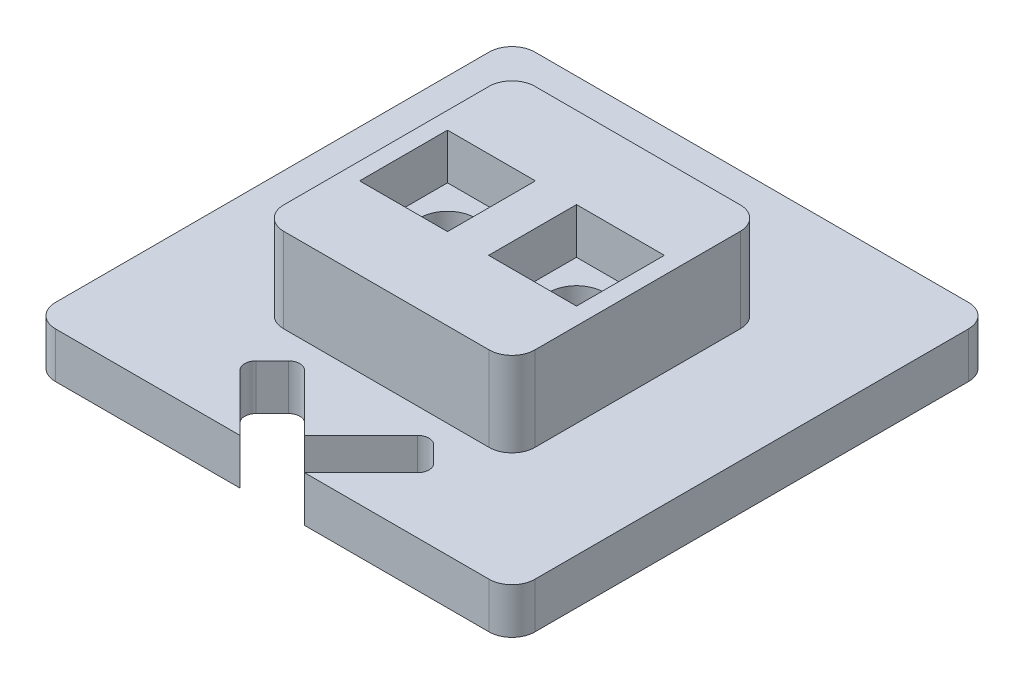
SolidWorks part; units mm, degrees
ref_plane "Front Plane" through (0, 0, 0) normal (0, 0, 1) x (1, 0, 0)
ref_plane "Top Plane" through (0, 0, 0) normal (0, 1, 0) x (1, 0, 0)
ref_plane "Right Plane" through (0, 0, 0) normal (1, 0, 0) x (0, 0, -1)
sketch "Sketch1" plane through (0, 0, 0) normal (0, 1, 0) x (1, 0, 0)
  line L1 (-5.5, -5.5) -> (5.5, -5.5)
  line L2 (-5.5, -5.5) -> (-5.5, 5.5)
  line L3 (-5.5, 5.5) -> (5.5, 5.5)
  line L4 (5.5, -5.5) -> (5.5, 5.5)
  line L5 (-5.5, -5.5) -> (5.5, 5.5) construction
  line L6 (-5.5, 5.5) -> (5.5, -5.5) construction
  point P0 (0, 0)
  dimension "D1" = 11
  dimension "D2" = 11
extrude "Boss-Extrude1" add sketch "Sketch1" along normal blind 3.7
fillet "Fillet1" radius 1 4 edges at (-5.5, 1.85, -5.5) (-5.5, 1.85, 5.5) (5.5, 1.85, -5.5) (5.5, 1.85, 5.5)
sketch "Sketch2" plane through (0, 3.7, 0) normal (0, 1, 0) x (1, 0, 0)
  line L0 (-2.825, 0) -> (2.825, 0) construction
  line L2 (-4.75, -1.925) -> (-0.9, -1.925)
  line L3 (-4.75, -1.925) -> (-4.75, 1.925)
  line L4 (-4.75, 1.925) -> (-0.9, 1.925)
  line L5 (-0.9, -1.925) -> (-0.9, 1.925)
  line L6 (-4.75, -1.925) -> (-0.9, 1.925) construction
  line L7 (-4.75, 1.925) -> (-0.9, -1.925) construction
  line L8 (0.9, -1.925) -> (4.75, -1.925)
  line L9 (0.9, -1.925) -> (0.9, 1.925)
  line L10 (0.9, 1.925) -> (4.75, 1.925)
  line L11 (4.75, -1.925) -> (4.75, 1.925)
  line L12 (0.9, -1.925) -> (4.75, 1.925) construction
  line L13 (0.9, 1.925) -> (4.75, -1.925) construction
  point P4 (0, 0)
  dimension "D1" = 3.85
  dimension "D2" = 3.85
  dimension "D3" = 3.85
  dimension "D4" = 3.85
  dimension "D5" = 5.65
extrude "Cut-Extrude1" cut sketch "Sketch2" against normal blind 2
sketch "Sketch4" plane through (0, 0, 0) normal (0, -1, 0) x (-1, 0, 0)
  line L0 (2.825, 0) -> (-2.825, 0) construction
  circle A0 centre (2.825, 0) radius 2.2
  circle A1 centre (-2.825, 0) radius 2.2
  point P4 (0, 0)
  point P8 (0, 0)
  dimension "D1" = 5.65
  dimension "D2" = 4.4
  dimension "D3" = 4.4
extrude "Boss-Extrude2" add sketch "Sketch4" along normal blind 2
sketch "Sketch5" plane through (0, -2, 0) normal (0, -1, 0) x (-1, 0, 0)
  line L1 (9.5, 10.5) -> (-9.5, 10.5)
  line L2 (10.5, 9.5) -> (10.5, -9.5)
  line L3 (9.5, -10.5) -> (-9.5, -10.5)
  line L4 (-10.5, 9.5) -> (-10.5, -9.5)
  line L5 (10.5, 10.5) -> (-10.5, -10.5) construction
  line L6 (10.5, -10.5) -> (-10.5, 10.5) construction
  arc A0 (10.5, -9.5) -> (9.5, -10.5) centre (9.5, -9.5) cw
  arc A1 (-10.5, -9.5) -> (-9.5, -10.5) centre (-9.5, -9.5) ccw
  arc A2 (-9.5, 10.5) -> (-10.5, 9.5) centre (-9.5, 9.5) ccw
  arc A3 (9.5, 10.5) -> (10.5, 9.5) centre (9.5, 9.5) cw
  point P0 (0, 0)
  dimension "D3" = 1
  dimension "D1" = 21
  dimension "D2" = 21
extrude "Boss-Extrude3" add sketch "Sketch5" against normal blind 2
sketch "Sketch3" plane through (0, 3.7, 0) normal (0, 1, 0) x (1, 0, 0)
  line L0 (-2.825, 0) -> (2.825, 0) construction
  circle A0 centre (-2.825, 0) radius 1.2
  circle A1 centre (2.825, 0) radius 1.2
  point P4 (0, 0)
  point P5 (0, 0)
  point P8 (0, 0)
  dimension "D2" = 2.4
  dimension "D3" = 2.4
  dimension "D1" = 5.65
extrude "Cut-Extrude2" cut sketch "Sketch3" against normal through all
sketch "Sketch7" plane through (0, 0, 0) normal (0, 1, 0) x (1, 0, 0)
  line L0 (9.5, -10.5) -> (-9.5, -10.5) construction
  line L1 (2.8284, -14.7426) -> (4.2426, -13.3284)
  line L2 (2.8284, -14.7426) -> (-3.8891, -8.0251)
  line L3 (-3.8891, -7.318) -> (-3.182, -6.6109)
  line L4 (4.2426, -13.3284) -> (-2.4749, -6.6109)
  line L5 (2.8284, -14.7426) -> (-2.8284, -6.2574) construction
  line L6 (-4.2426, -7.6716) -> (4.2426, -13.3284) construction
  line L8 (-4.2426, -13.3284) -> (-2.8284, -14.7426)
  line L9 (-4.2426, -13.3284) -> (2.4749, -6.6109)
  line L10 (3.182, -6.6109) -> (3.8891, -7.318)
  line L11 (-2.8284, -14.7426) -> (3.8891, -8.0251)
  line L12 (-4.2426, -13.3284) -> (4.2426, -7.6716) construction
  line L13 (2.8284, -6.2574) -> (-2.8284, -14.7426) construction
  arc A0 (-2.4749, -6.6109) -> (-3.182, -6.6109) centre (-2.8284, -6.9645) ccw
  arc A1 (3.8891, -7.318) -> (3.8891, -8.0251) centre (3.5355, -7.6716) cw
  arc A2 (3.182, -6.6109) -> (2.4749, -6.6109) centre (2.8284, -6.9645) ccw
  arc A3 (-3.8891, -7.318) -> (-3.8891, -8.0251) centre (-3.5355, -7.6716) ccw
  point P0 (0, -10.5)
  point P7 (0, -10.5)
  point P12 (-1.4142, -10.5)
  point P13 (1.4142, -10.5)
  line M12 (-9.5, -10.5) -> (9.5, -10.5)
  dimension "D7" = 0.5
  dimension "D8" = 0.5
  dimension "D1" = 2
  dimension "D2" = 45
  dimension "D3" = 2
  dimension "D4" = 45
  dimension "D5" = 4
  dimension "D6" = 4
extrude "Cut-Extrude3" cut sketch "Sketch7" against normal through all contours L10 A2 L9 L4 L11 A1 | L3 A3 L2 L9 L4 A0 | L9 L4 M12
equation "\"D2@Sketch2\"=\"D1@Sketch2\""
equation "\"D3@Sketch2\"=\"D1@Sketch2\""
equation "\"D4@Sketch2\"=\"D1@Sketch2\""
equation "\"D2@Sketch1\"=\"D1@Sketch1\""
equation "\"D3@Sketch3\"=\"D2@Sketch3\""
equation "\"D3@Sketch4\"=\"D2@Sketch4\""
equation "\"D2@Sketch5\"=\"D1@Sketch5\""
equation "\"D3@Sketch7\"=\"D1@Sketch7\""
equation "\"D6@Sketch7\"=\"D5@Sketch7\""
